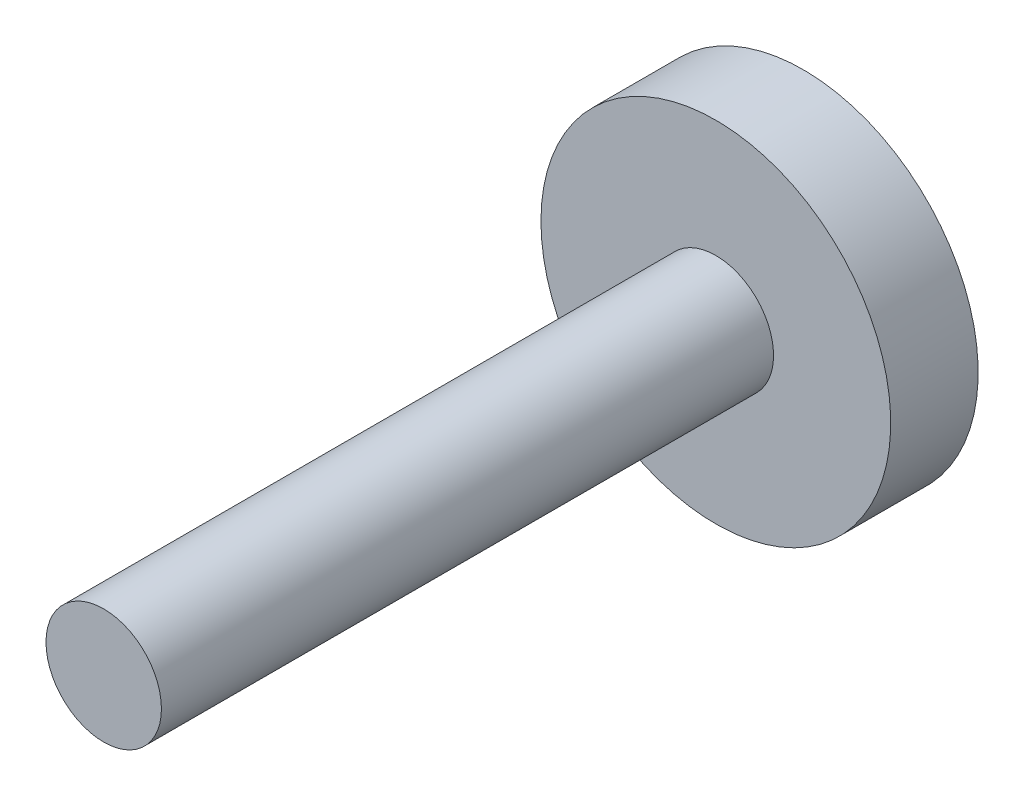
SolidWorks part; units mm, degrees
ref_plane "Front Plane" through (0, 0, 0) normal (0, 0, 1) x (1, 0, 0)
ref_plane "Top Plane" through (0, 0, 0) normal (0, 1, 0) x (1, 0, 0)
ref_plane "Right Plane" through (0, 0, 0) normal (1, 0, 0) x (0, 0, -1)
sketch "Sketch1" plane through (0, 0, 0) normal (0, 0, 1) x (1, 0, 0)
  circle A0 centre (0, 0) radius 1.65
  dimension "D1" = 3.3
extrude "Boss-Extrude1" add sketch "Sketch1" along normal blind 20
sketch "Sketch2" plane through (0, 0, 0) normal (0, 0, -1) x (-1, 0, 0)
  circle A0 centre (0, 0) radius 5
  dimension "D1" = 10
extrude "Boss-Extrude2" add sketch "Sketch2" against normal blind 2.5
